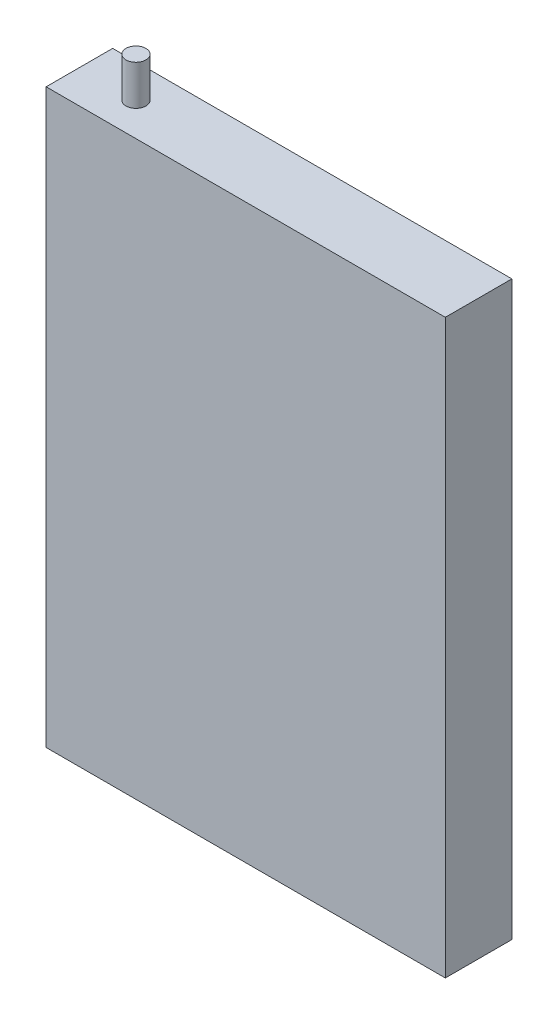
SolidWorks part; units mm, degrees
ref_plane "Front Plane" through (0, 0, 0) normal (0, 0, 1) x (1, 0, 0)
ref_plane "Top Plane" through (0, 0, 0) normal (0, 1, 0) x (1, 0, 0)
ref_plane "Right Plane" through (0, 0, 0) normal (1, 0, 0) x (0, 0, -1)
sketch "Sketch1" plane through (0, 0, 0) normal (0, 0, 1) x (1, 0, 0)
  line L1 (0, 0) -> (60, 0)
  line L2 (0, 0) -> (0, -86)
  line L3 (0, -86) -> (60, -86)
  line L4 (60, 0) -> (60, -86)
  dimension "D1" = 86
  dimension "D2" = 60
extrude "Boss-Extrude1" add sketch "Sketch1" along normal blind 10
sketch "Sketch2" plane through (0, 0, 0) normal (0, 1, 0) x (1, 0, 0)
  line L0 (0, -5) -> (60, -5) construction
  line L1 (0, -10) -> (0, 0) construction
  line L2 (60, -10) -> (60, 0) construction
  circle A0 centre (8.5, -5) radius 1.5
  dimension "D1" = 3
  dimension "D2" = 8.5
extrude "Boss-Extrude2" add sketch "Sketch2" along normal blind 6
